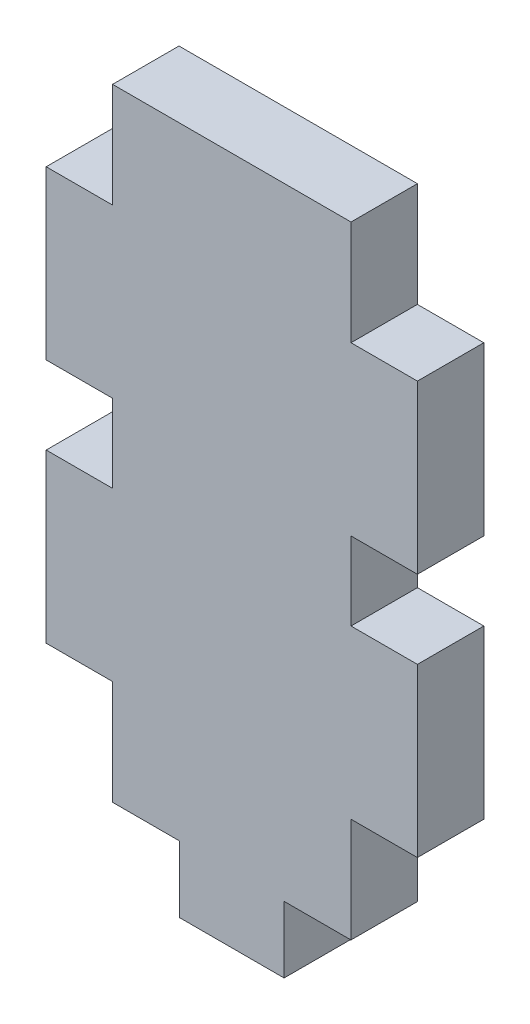
SolidWorks part; units mm, degrees
ref_plane "Front Plane" through (0, 0, 0) normal (0, 0, 1) x (1, 0, 0)
ref_plane "Top Plane" through (0, 0, 0) normal (0, 1, 0) x (1, 0, 0)
ref_plane "Right Plane" through (0, 0, 0) normal (1, 0, 0) x (0, 0, -1)
sketch "Sketch1" plane through (0, 0, 0) normal (0, 0, 1) x (1, 0, 0)
  line L0 (0, -14.865) -> (0, -12.1166)
  line L1 (-5.7, -14.865) -> (5.7, -14.865)
  line L2 (-5.7, -14.865) -> (-5.7, 14.865)
  line L3 (-5.7, 14.865) -> (5.7, 14.865)
  line L4 (5.7, -14.865) -> (5.7, 14.865)
  line L5 (-5.7, -14.865) -> (5.7, 14.865) construction
  line L6 (-5.7, 14.865) -> (5.7, -14.865) construction
  line L7 (-5.7, 9.865) -> (-8.875, 9.865)
  line L8 (-5.7, 9.865) -> (-5.7, 1.865)
  line L9 (-5.7, 1.865) -> (-8.875, 1.865)
  line L10 (-8.875, 9.865) -> (-8.875, 1.865)
  line L11 (-5.7, -1.865) -> (-8.875, -1.865)
  line L12 (-5.7, -1.865) -> (-5.7, -9.865)
  line L13 (-5.7, -9.865) -> (-8.875, -9.865)
  line L14 (-8.875, -1.865) -> (-8.875, -9.865)
  line L15 (5.7, 9.865) -> (8.875, 9.865)
  line L16 (5.7, 9.865) -> (5.7, 1.865)
  line L17 (5.7, 1.865) -> (8.875, 1.865)
  line L18 (8.875, 9.865) -> (8.875, 1.865)
  line L19 (5.7, -1.865) -> (8.875, -1.865)
  line L20 (5.7, -1.865) -> (5.7, -9.865)
  line L21 (5.7, -9.865) -> (8.875, -9.865)
  line L22 (8.875, -1.865) -> (8.875, -9.865)
  line L23 (0, -14.865) -> (2.5, -14.865)
  line L24 (0, -14.865) -> (0, -18.04)
  line L25 (0, -18.04) -> (2.5, -18.04)
  line L26 (2.5, -14.865) -> (2.5, -18.04)
  line L28 (0, -14.865) -> (-2.5, -14.865)
  line L29 (0, -14.865) -> (0, -18.04)
  line L30 (0, -18.04) -> (-2.5, -18.04)
  line L31 (-2.5, -14.865) -> (-2.5, -18.04)
  point P0 (0, 0)
  dimension "D1" = 3.175
  dimension "D2" = 3.175
  dimension "D3" = 3.175
  dimension "D4" = 3.175
  dimension "D5" = 29.73
  dimension "D6" = 5
  dimension "D7" = 5
  dimension "D8" = 8
  dimension "D9" = 8
  dimension "D10" = 5
  dimension "D11" = 8
  dimension "D12" = 5
  dimension "D13" = 8
  dimension "D14" = 3.175
  dimension "D15" = 2.5
  dimension "D16" = 2.5
  dimension "D17" = 11.4
extrude "Boss-Extrude1" add sketch "Sketch1" along normal blind 3.175
